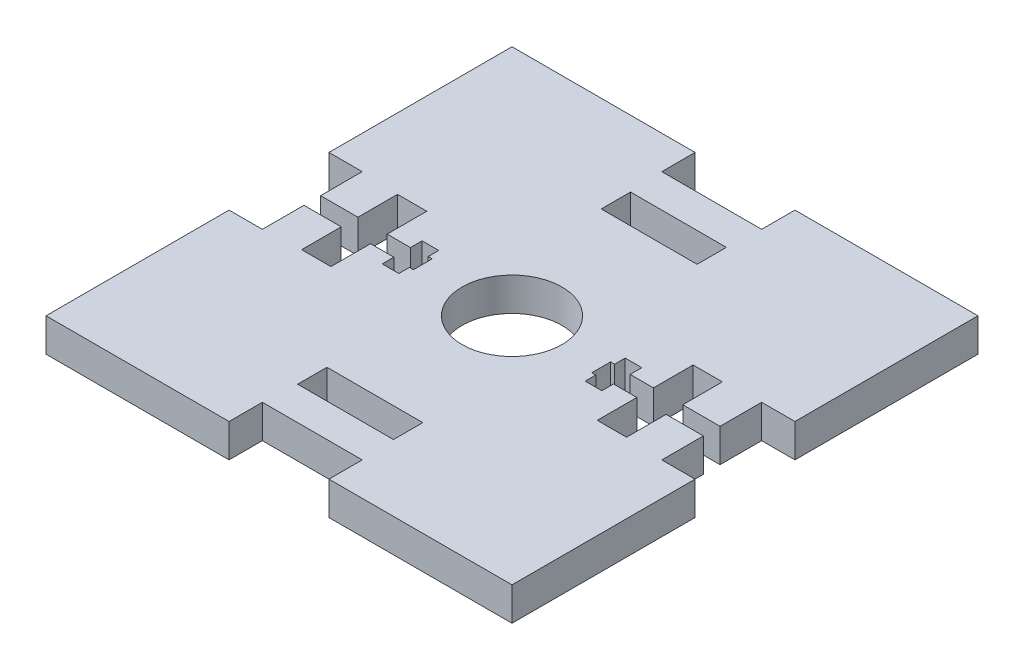
SolidWorks part; units mm, degrees
ref_plane "Front Plane" through (0, 0, 0) normal (0, 0, 1) x (1, 0, 0)
ref_plane "Top Plane" through (0, 0, 0) normal (0, 1, 0) x (1, 0, 0)
ref_plane "Right Plane" through (0, 0, 0) normal (1, 0, 0) x (0, 0, -1)
sketch "Sketch1" plane through (0, 0, 0) normal (0, 1, 0) x (1, 0, 0)
  line L1 (0, 0) -> (88.9, 0)
  line L2 (0, 0) -> (0, 88.9)
  line L3 (0, 88.9) -> (88.9, 88.9)
  line L4 (88.9, 0) -> (88.9, 88.9)
  dimension "D1" = 88.9
  dimension "D2" = 88.9
extrude "Boss-Extrude1" add sketch "Sketch1" along normal blind 6.35
sketch "Sketch2" plane through (0, 6.35, 0) normal (0, 1, 0) x (1, 0, 0)
  line L0 (88.9, 88.9) -> (0, 88.9) construction
  line L5 (35.306, 76.2) -> (53.594, 76.2)
  line L6 (35.306, 76.2) -> (35.306, 70.612)
  line L7 (35.306, 70.612) -> (53.594, 70.612)
  line L8 (53.594, 76.2) -> (53.594, 70.612)
  line L9 (13.462, 53.594) -> (19.05, 53.594)
  line L10 (13.462, 53.594) -> (13.462, 35.306)
  line L11 (13.462, 35.306) -> (19.05, 35.306)
  line L12 (19.05, 53.594) -> (19.05, 35.306)
  line L13 (88.9, 0) -> (88.9, 88.9) construction
  line L14 (-3.4925, 0) -> (3.4925, 0) construction
  line L15 (44.45, 88.9) -> (44.45, 0) construction
  line L16 (0, 44.45) -> (88.9, 44.45) construction
  line L17 (69.85, 53.594) -> (69.85, 35.306)
  line L18 (75.438, 35.306) -> (69.85, 35.306)
  line L19 (75.438, 53.594) -> (75.438, 35.306)
  line L20 (75.438, 53.594) -> (69.85, 53.594)
  line L21 (53.594, 12.7) -> (53.594, 18.288)
  line L22 (35.306, 18.288) -> (53.594, 18.288)
  line L23 (35.306, 12.7) -> (35.306, 18.288)
  line L24 (35.306, 12.7) -> (53.594, 12.7)
  line L25 (0, -3.4925) -> (0, 3.4925) construction
  circle A0 centre (44.45, 44.45) radius 9.525
  point P2 (19.05, 44.45)
  point P3 (44.45, 70.612)
  point P28 (44.45, 44.45)
  point P29 (44.45, 57.15)
  point P34 (57.15, 44.45)
  point P35 (69.85, 44.45)
  point P36 (44.45, 18.288)
  dimension "D5" = 19.05
  dimension "D1" = 18.288
  dimension "D2" = 5.588
  dimension "D3" = 5.588
  dimension "D4" = 18.288
  dimension "D6" = 31.75
  dimension "D11" = 25.4
extrude "Cut-Extrude1" cut sketch "Sketch2" against normal through all
sketch "Sketch3" plane through (0, 6.35, 0) normal (0, 1, 0) x (1, 0, 0)
  line L0 (88.9, 88.9) -> (0, 88.9) construction
  line L1 (34.925, 88.9) -> (53.975, 88.9)
  line L2 (34.925, 88.9) -> (34.925, 82.55)
  line L3 (34.925, 82.55) -> (53.975, 82.55)
  line L4 (53.975, 88.9) -> (53.975, 82.55)
  line L6 (0, 44.45) -> (88.9, 44.45) construction
  line L7 (88.9, 88.9) -> (0, 88.9) construction
  line L8 (44.45, 88.9) -> (44.45, 0) construction
  line L10 (82.55, 53.975) -> (82.55, 34.925)
  line L11 (88.9, 34.925) -> (82.55, 34.925)
  line L12 (88.9, 53.975) -> (88.9, 34.925)
  line L13 (88.9, 53.975) -> (82.55, 53.975)
  line L14 (53.975, 6.35) -> (34.925, 6.35)
  line L15 (34.925, 0) -> (34.925, 6.35)
  line L16 (53.975, 0) -> (34.925, 0)
  line L17 (53.975, 0) -> (53.975, 6.35)
  line L18 (6.35, 34.925) -> (6.35, 53.975)
  line L19 (0, 53.975) -> (6.35, 53.975)
  line L20 (0, 34.925) -> (0, 53.975)
  line L21 (0, 34.925) -> (6.35, 34.925)
  point P18 (44.45, 44.45)
  point P19 (44.45, 88.9)
  point P27 (88.9, 44.45)
  point P32 (44.45, 0)
  point P37 (0, 44.45)
  point P38 (44.45, 44.45)
  dimension "D1" = 6.35
  dimension "D2" = 19.05
  dimension "D4" = 4
extrude "Cut-Extrude2" cut sketch "Sketch3" against normal through all
sketch "Sketch4" plane through (0, 6.35, 0) normal (0, 1, 0) x (1, 0, 0)
  line L0 (0, 44.45) -> (88.9, 44.45) construction
  line L1 (19.05, 53.594) -> (19.05, 35.306) construction
  line L2 (23.495, 46.0375) -> (23.495, 48.26)
  line L3 (44.45, 88.9) -> (44.45, 0) construction
  line L4 (44.45, 88.9) -> (44.45, 0) construction
  line L5 (26.67, 46.2492) -> (27.432, 46.2492)
  line L6 (82.55, 46.0375) -> (62.23, 42.6508) construction
  line L7 (23.495, 40.64) -> (26.67, 40.64)
  line L8 (23.495, 40.64) -> (23.495, 42.8625)
  line L9 (23.495, 48.26) -> (26.67, 48.26)
  line L10 (26.67, 46.2492) -> (26.67, 48.26)
  line L11 (23.495, 40.64) -> (26.67, 48.26) construction
  line L12 (23.495, 48.26) -> (26.67, 40.64) construction
  line L13 (82.55, 42.8625) -> (62.23, 46.2492) construction
  line L14 (62.23, 46.2492) -> (61.468, 46.2492)
  line L15 (6.35, 42.8625) -> (23.495, 42.8625)
  line L16 (6.35, 42.8625) -> (6.35, 46.0375)
  line L17 (6.35, 46.0375) -> (23.495, 46.0375)
  line L18 (27.432, 46.2492) -> (27.432, 42.6508)
  line L19 (6.35, 42.8625) -> (26.67, 46.2492) construction
  line L20 (6.35, 46.0375) -> (26.67, 42.6508) construction
  line L21 (65.405, 48.26) -> (62.23, 40.64) construction
  line L22 (65.405, 40.64) -> (62.23, 48.26) construction
  line L23 (62.23, 42.6508) -> (62.23, 40.64)
  line L24 (69.85, 53.594) -> (69.85, 35.306) construction
  line L25 (27.432, 42.6508) -> (26.67, 42.6508)
  line L26 (61.468, 46.2492) -> (61.468, 42.6508)
  line L27 (82.55, 46.0375) -> (65.405, 46.0375)
  line L28 (82.55, 42.8625) -> (82.55, 46.0375)
  line L29 (82.55, 42.8625) -> (65.405, 42.8625)
  line L30 (61.468, 42.6508) -> (62.23, 42.6508)
  line L33 (26.67, 42.6508) -> (26.67, 40.64)
  line L34 (62.23, 46.2492) -> (62.23, 48.26)
  line L35 (65.405, 48.26) -> (62.23, 48.26)
  line L36 (65.405, 40.64) -> (65.405, 42.8625)
  line L37 (65.405, 40.64) -> (62.23, 40.64)
  line L38 (65.405, 46.0375) -> (65.405, 48.26)
  line L71 (6.35, 34.925) -> (6.35, 53.975) construction
  line L73 (6.35, 34.925) -> (6.35, 53.975) construction
  point P0 (25.0825, 44.45)
  point P5 (25.0825, 44.45)
  point P14 (15.875, 44.45)
  point P37 (73.025, 44.45)
  point P38 (63.8175, 44.45)
  dimension "D1" = 3.175
  dimension "D2" = 6.0325
  dimension "D3" = 3.175
  dimension "D4" = 7.62
  dimension "D6" = 18.7325
  dimension "D5" = 6.0325
  dimension "D7" = 18.7325
  dimension "D8" = 0.762
  dimension "D9" = 0.762
extrude "Cut-Extrude3" cut sketch "Sketch4" against normal through all
